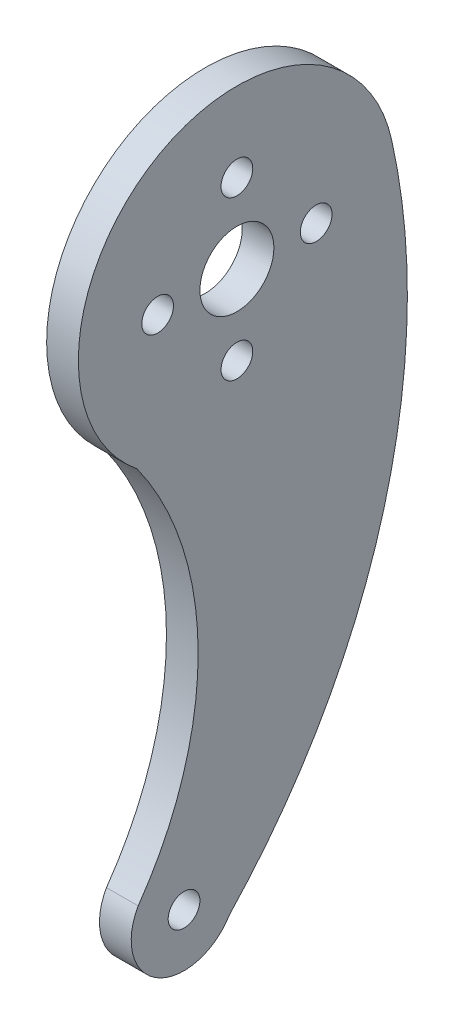
SolidWorks part; units mm, degrees
ref_plane "Alzado" through (0, 0, 0) normal (0, 0, 1) x (1, 0, 0)
ref_plane "Planta" through (0, 0, 0) normal (0, 1, 0) x (1, 0, 0)
ref_plane "Vista lateral" through (0, 0, 0) normal (1, 0, 0) x (0, 0, -1)
sketch "Croquis1" plane through (0, 0, 0) normal (1, 0, 0) x (0, 0, -1)
  line L0 (0, 0) -> (0, -50) construction
  line L1 (0, -50) -> (-5, -50) construction
  line L3 (0, 0) -> (0, 21.7358) construction
  arc A0 (14.6577, 3.1863) -> (-9.4496, -11.6493) centre (0, 0) ccw
  arc A1 (-9.3383, -47.5143) -> (-0.7107, -52.5695) centre (-5, -50) ccw
  arc A2 (14.6577, 3.1863) -> (-0.7107, -52.5695) centre (-45.5953, -10.2016) cw
  arc A3 (-9.3383, -47.5143) -> (-9.4496, -11.6493) centre (-34.6008, -29.6599) ccw
  circle A4 centre (0, 0) radius 3.5
  circle A5 centre (-5, -50) radius 1.5
  circle A7 centre (-7.5, 0) radius 1.5
  circle A8 centre (0, 7.5) radius 1.5
  circle A9 centre (7.5, 0) radius 1.5
  circle A10 centre (0, -7.5) radius 1.5
  dimension "D1" = 50
  dimension "D2" = 15
  dimension "D3" = 7
  dimension "D4" = 3
extrude "Saliente-Extruir1" add sketch "Croquis1" along normal blind 3
